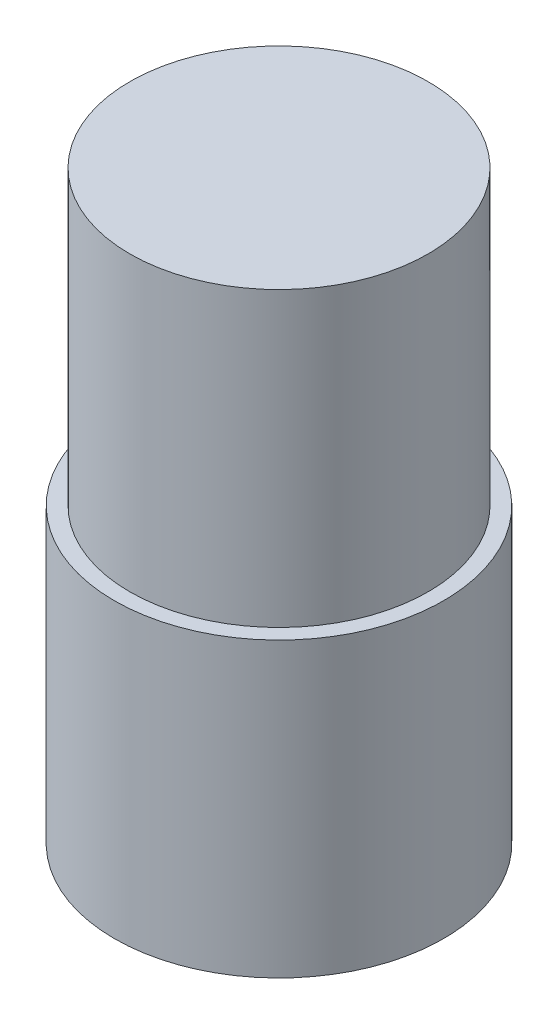
SolidWorks part; units mm, degrees
material "PUR"
ref_plane "Z" through (0, 0, 0) normal (0, 0, 1) x (1, 0, 0)
ref_plane "Y" through (0, 0, 0) normal (0, 1, 0) x (1, 0, 0)
ref_plane "X" through (0, 0, 0) normal (1, 0, 0) x (0, 0, -1)
sketch "Sketch1" plane through (0, 0, 0) normal (0, 1, 0) x (1, 0, 0)
  circle A0 centre (0, 0) radius 7.1438
  dimension "D1" = 14.2875
extrude "Boss-Extrude1" add sketch "Sketch1" along normal blind 25.4
sketch "Sketch2" plane through (0, 25.4, 0) normal (0, 1, 0) x (1, 0, 0)
  circle A0 centre (0, 0) radius 6.475
  circle A1 centre (0, 0) radius 7.8362
  dimension "D1" = 12.95
extrude "Cut-Extrude1" cut sketch "Sketch2" against normal blind 12.7
